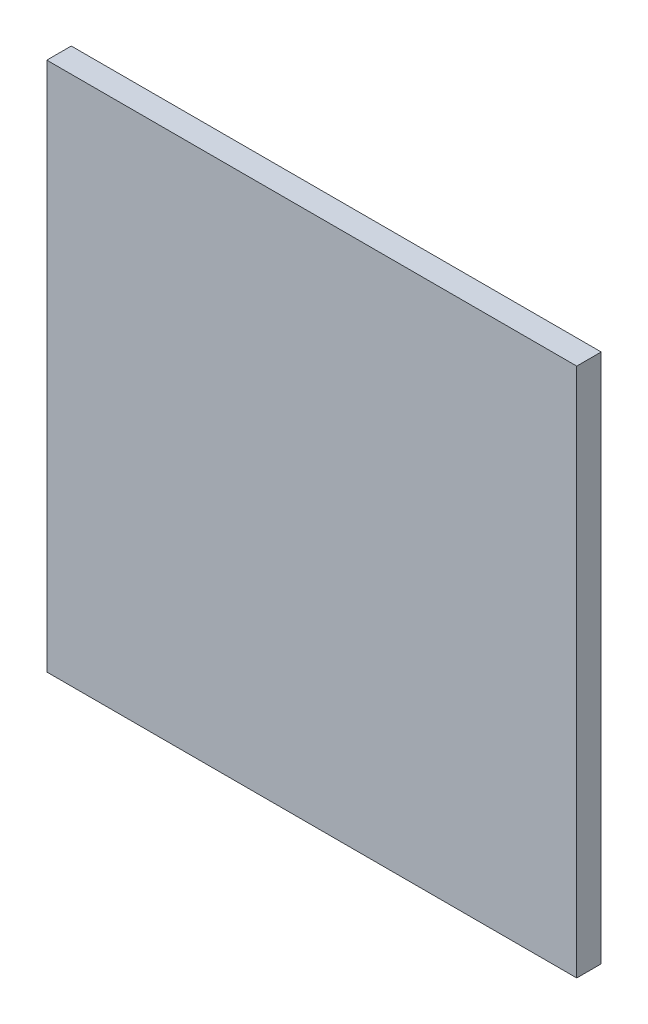
SolidWorks part; units mm, degrees
ref_plane "Front Plane" through (0, 0, 0) normal (0, 0, 1) x (1, 0, 0)
ref_plane "Top Plane" through (0, 0, 0) normal (0, 1, 0) x (1, 0, 0)
ref_plane "Right Plane" through (0, 0, 0) normal (1, 0, 0) x (0, 0, -1)
sketch "Sketch1" plane through (0, 0, 0) normal (0, 0, 1) x (1, 0, 0)
  line L1 (-32.5, -32.5) -> (32.5, -32.5)
  line L2 (-32.5, -32.5) -> (-32.5, 32.5)
  line L3 (-32.5, 32.5) -> (32.5, 32.5)
  line L4 (32.5, -32.5) -> (32.5, 32.5)
  line L5 (-32.5, -32.5) -> (32.5, 32.5) construction
  line L6 (-32.5, 32.5) -> (32.5, -32.5) construction
  point P0 (0, 0)
  dimension "D1" = 65
  dimension "D2" = 65
extrude "Boss-Extrude1" add sketch "Sketch1" along normal blind 3
